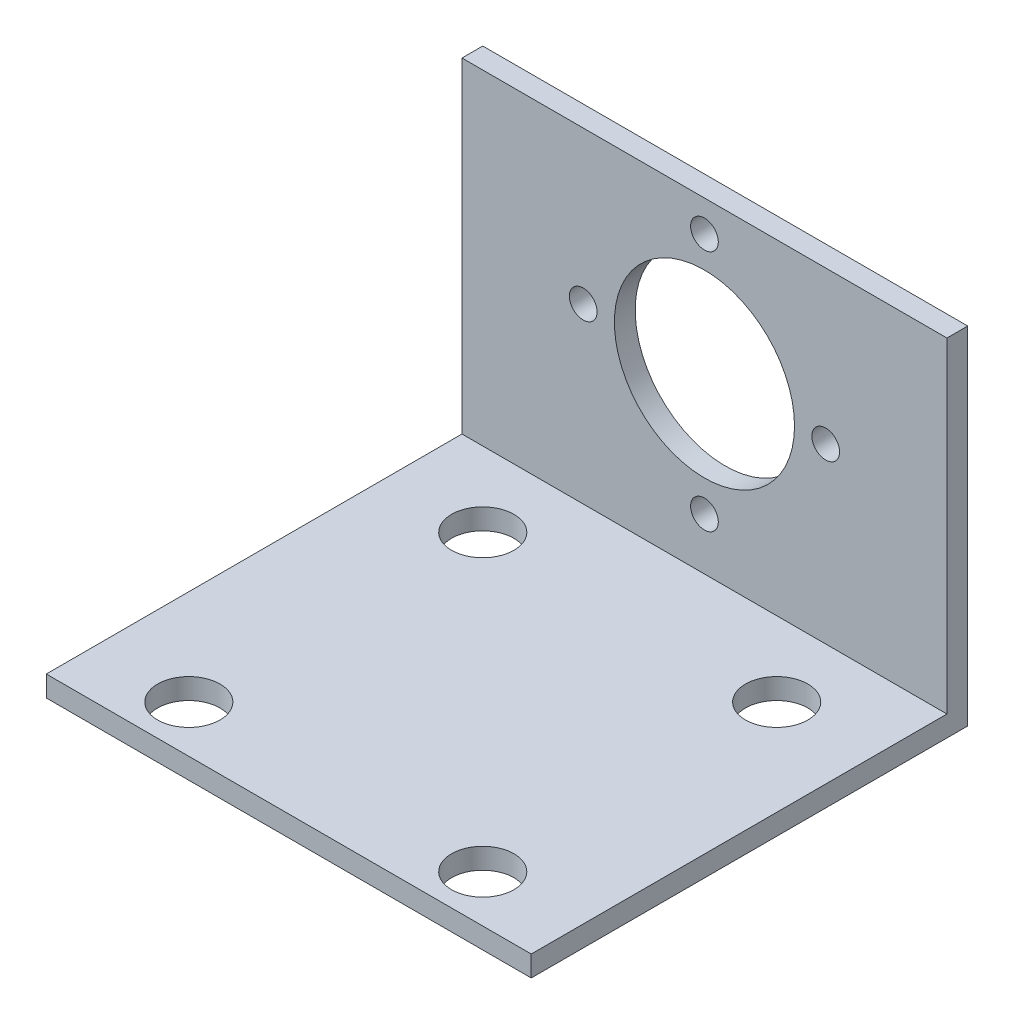
SolidWorks part; units mm, degrees
ref_plane "前视基准面" through (0, 0, 0) normal (0, 0, 1) x (1, 0, 0)
ref_plane "上视基准面" through (0, 0, 0) normal (0, 1, 0) x (1, 0, 0)
ref_plane "右视基准面" through (0, 0, 0) normal (1, 0, 0) x (0, 0, -1)
sketch "草图1" plane through (0, 0, 0) normal (0, 0, 1) x (1, 0, 0)
  line L0 (0, 22.6169) -> (0, -23.1499) construction
  line L1 (-35, 22) -> (35, 22)
  line L2 (-35, 22) -> (-35, 0)
  line L5 (-28.4064, 0) -> (21.9371, 0) construction
  line L6 (35, 22) -> (35, -28)
  line L7 (-35, 0) -> (-35, -28)
  line L8 (-35, -28) -> (35, -28)
  circle A0 centre (0, 0) radius 13
  circle A1 centre (0, 0) radius 17.5 construction
  circle A2 centre (0, 17.5) radius 2
  circle A3 centre (17.5, 0) radius 2
  circle A4 centre (0, -17.5) radius 2
  circle A5 centre (-17.5, 0) radius 2
  point P14 (0, 22)
  point P25 (0, 0)
  dimension "D1" = 28
  dimension "D3" = 4
  dimension "D2" = 35
extrude "凸台-拉伸1" add sketch "草图1" along normal blind 3
sketch "草图2" plane through (0, 0, 3) normal (0, 0, 1) x (1, 0, 0)
  line L0 (35, -28) -> (35, 22) construction
  line L1 (-35, -28) -> (35, -28)
  line L2 (-35, -28) -> (-35, -25)
  line L3 (-35, -25) -> (35, -25)
  line L4 (35, -28) -> (35, -25)
extrude "凸台-拉伸2" add sketch "草图2" along normal blind 60
sketch "草图3" plane through (0, -25, 0) normal (0, 1, 0) x (1, 0, 0)
  line L0 (0, -64.9636) -> (0, -5.0364) construction
  line L1 (0, -35) -> (21.2132, -13.7868) construction
  line L6 (35, -63) -> (-35, -63) construction
  circle A4 centre (0, -35) radius 30 construction
  circle A9 centre (21.2132, -13.7868) radius 4.5
  circle A10 centre (21.2132, -56.2132) radius 4.5
  circle A11 centre (-21.2132, -56.2132) radius 4.5
  circle A12 centre (-21.2132, -13.7868) radius 4.5
  point P16 (0, -29.9791)
  point P19 (0, -35)
  dimension "D1" = 28
  dimension "D2" = 4
extrude "切除-拉伸1" cut sketch "草图3" against normal through all
